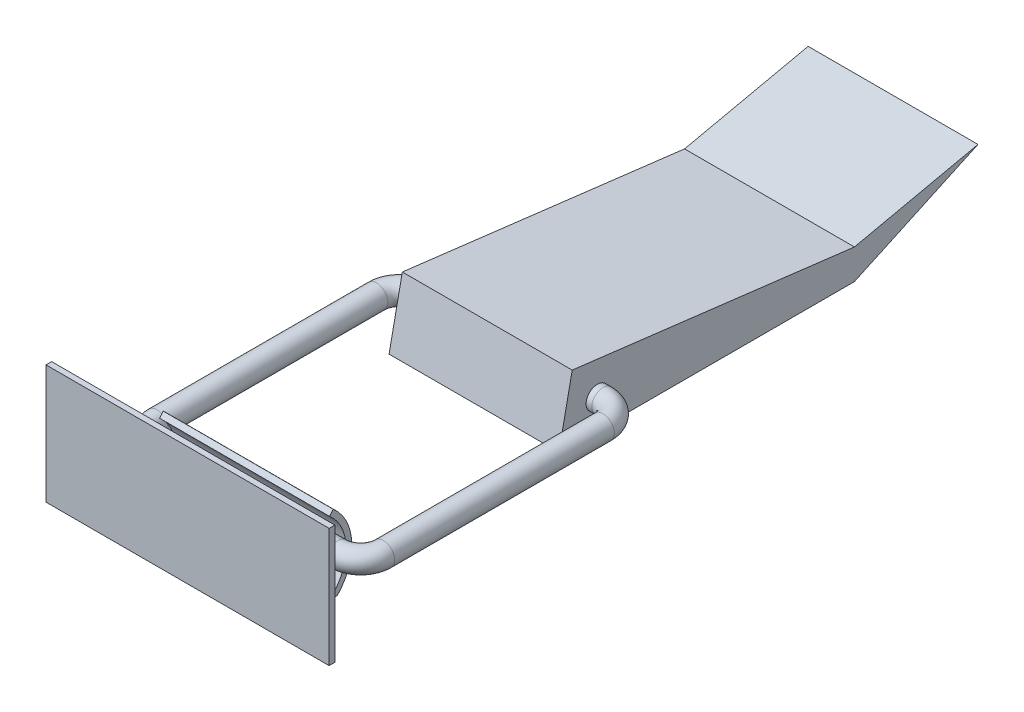
SolidWorks part; units mm, degrees
material "AISI 1020"
ref_plane "Front Plane" through (0, 0, 0) normal (0, 0, 1) x (1, 0, 0)
ref_plane "Top Plane" through (0, 0, 0) normal (0, 1, 0) x (1, 0, 0)
ref_plane "Right Plane" through (0, 0, 0) normal (1, 0, 0) x (0, 0, -1)
sketch "Sketch1" plane through (0, 0, 0) normal (1, 0, 0) x (0, 0, -1)
  line L0 (0, 0) -> (1.1719, 5.6964)
  line L1 (1.1719, 5.6964) -> (26.0909, 2.6497)
  line L2 (26.0909, 2.6497) -> (37, 5.0363)
  line L3 (37, 5.0363) -> (26.0909, 0)
  line L4 (26.0909, 0) -> (0, 0)
  point P3 (54.5682, 7.2386)
  point P7 (72.3864, 11.2159)
  point P8 (58.7045, 4.2159)
  point P9 (0, 0)
  point P10 (70, 6.125)
  point P11 (57, 17.8977)
  point P12 (26.0909, 0)
  point P13 (20.6921, 3.2907)
  point P14 (37, 5.0363)
  point P15 (26.0909, 2.6497)
  point P16 (1.1719, 5.6964)
  dimension "D1" = 37
extrude "Boss-Extrude1" add sketch "Sketch1" along normal blind 15
ref_plane "Plane1" through (0, 2.5, 0) normal (0, -1, 0) x (-1, 0, 0)
sketch "Sketch2" plane through (0, 2.5, 0) normal (0, -1, 0) x (-1, 0, 0)
  line L0 (-15, 3.3962) -> (-15.5, 3.3962)
  line L1 (-15, 0) -> (-15, 26.0909) construction
  line L2 (-17.5, 1.3962) -> (-17.5, -18)
  line L3 (-15.5, -20) -> (0.5, -20)
  line L4 (2.5, -18) -> (2.5, 1.3962)
  line L5 (0.5, 3.3962) -> (0, 3.3962)
  line L6 (0, 0) -> (0, 26.0909) construction
  line L7 (-7.5, 37) -> (-7.5, 0) construction
  line L8 (-15, 37) -> (0, 37) construction
  line L9 (-15, 0) -> (0, 0) construction
  arc A0 (2.5, 1.3962) -> (0.5, 3.3962) centre (0.5, 1.3962) ccw
  arc A1 (0.5, -20) -> (2.5, -18) centre (0.5, -18) ccw
  arc A2 (-15.5, -20) -> (-17.5, -18) centre (-15.5, -18) cw
  arc A3 (-15.5, 3.3962) -> (-17.5, 1.3962) centre (-15.5, 1.3962) ccw
  dimension "D2" = 2
  dimension "D1" = 57
  dimension "D3" = 20
sweep "Sweep1" add path "Sketch2" circular profile diameter 2 parameters "D3"=2
ref_plane "Plane2" through (7.5, 0, 0) normal (1, 0, 0) x (0, 0, -1)
sketch "Sketch13" plane through (7.5, 0, 0) normal (1, 0, 0) x (0, 0, -1)
  line L0 (-19.7906, -0.6742) -> (-24.7906, -0.6742)
  line L1 (-24.7906, -0.6742) -> (-24.7906, 9.3258)
  line L2 (-19.5676, -1.1742) -> (-25.2906, -1.1742)
  line L3 (-25.2906, -1.1742) -> (-25.2906, 9.3258)
  line L4 (-20.2602, 5.23) -> (-19.9358, 5.6104)
  line L5 (-25.2906, 9.3258) -> (-24.7906, 9.3258)
  arc A0 (-20.2602, 5.23) -> (-19.7906, -0.6742) centre (-22.9774, 2.0431) cw
  arc A1 (-19.9358, 5.6104) -> (-19.5676, -1.1742) centre (-22.9774, 2.0431) cw
  dimension "D1" = 5
  dimension "D2" = 10
  dimension "D3" = 0.5
extrude "Boss-Extrude2" add sketch "Sketch13" along normal mid plane 15 separate body
sketch "Sketch14" plane through (15, 0, 0) normal (1, 0, 0) x (0, 0, -1)
  line L0 (-25.2906, -1.1742) -> (-19.5676, -1.1742) construction
  line L1 (-25.2906, -1.1742) -> (-24.7906, -1.1742)
  line L6 (-19.7906, -0.6742) -> (-24.7906, -0.6742)
  line L7 (-24.7906, -0.6742) -> (-24.7906, 9.3258)
  line L8 (-24.7906, 9.3258) -> (-25.2906, 9.3258)
  line L9 (-25.2906, 9.3258) -> (-25.2906, -1.1742)
  line L10 (-25.2906, -1.1742) -> (-19.5676, -1.1742)
  line L11 (-19.9358, 5.6104) -> (-20.2602, 5.23)
  line L13 (-24.7906, -1.1742) -> (-24.7906, 9.3258)
  line L14 (-24.7906, 9.3258) -> (-25.2906, 9.3258)
  line L15 (-25.2906, 9.3258) -> (-25.2906, -1.1742)
  arc A2 (-19.7906, -0.6742) -> (-20.2602, 5.23) centre (-22.9774, 2.0431) ccw
  arc A3 (-19.5676, -1.1742) -> (-19.9358, 5.6104) centre (-22.9774, 2.0431) ccw
  dimension "D1" = 0
extrude "Boss-Extrude3" add sketch "Sketch14" along normal blind 5 and the other way blind 20
